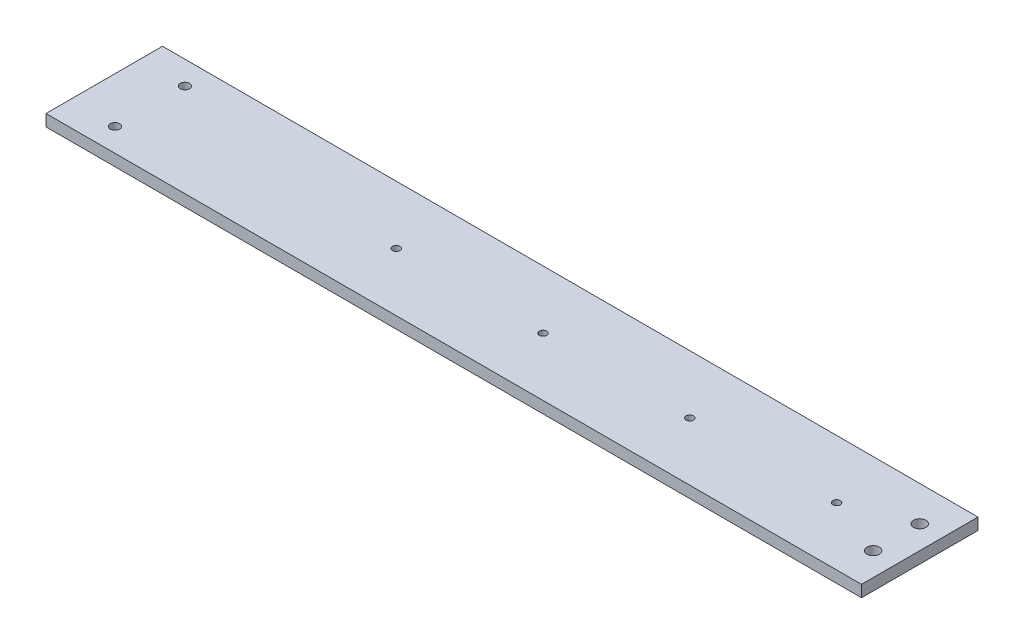
SolidWorks part; units mm, degrees
ref_plane "Front Plane" through (0, 0, 0) normal (0, 0, 1) x (1, 0, 0)
ref_plane "Top Plane" through (0, 0, 0) normal (0, 1, 0) x (1, 0, 0)
ref_plane "Right Plane" through (0, 0, 0) normal (1, 0, 0) x (0, 0, -1)
sketch "Sketch1" plane through (0, 0, 0) normal (0, 1, 0) x (1, 0, 0)
  line L1 (50.8, -25.4) -> (444.5, -25.4)
  line L2 (0, 0) -> (0, 12.7)
  line L3 (50.8, 38.1) -> (444.5, 38.1)
  line L4 (444.5, -25.4) -> (444.5, 38.1)
  line L6 (0, 0) -> (0, -25.4)
  line L7 (0, -25.4) -> (50.8, -25.4)
  line L10 (0, 12.7) -> (0, 38.1)
  line L11 (0, 38.1) -> (50.8, 38.1)
  dimension "D1" = 444.5
  dimension "D7" = 63.5
extrude "Boss-Extrude1" add sketch "Sketch1" along normal blind 6.35
sketch "Sketch2" plane through (0, 6.35, 0) normal (0, 1, 0) x (1, 0, 0)
  line L0 (0, 6.35) -> (444.5, 6.35) construction
  line L1 (0, 38.1) -> (0, -25.4) construction
  line L2 (444.5, -25.4) -> (444.5, 38.1) construction
  line L3 (431.8, -6.35) -> (431.8, 19.05) construction
  circle A0 centre (431.8, -6.35) radius 3.3734
  circle A1 centre (431.8, 19.05) radius 3.3734
  dimension "D1" = 6.7469
  dimension "D2" = 12.7
  dimension "D3" = 25.4
  dimension "D4" = 12.7
extrude "Cut-Extrude1" cut sketch "Sketch2" against normal through all
sketch "Sketch3" plane through (0, 6.35, 0) normal (0, 1, 0) x (1, 0, 0)
  line L0 (24.892, 25.4) -> (24.892, -12.7) construction
  line L1 (0, 38.1) -> (0, -25.4) construction
  circle A0 centre (24.892, 25.4) radius 1.27
  circle A1 centre (24.892, -12.7) radius 1.27
  point P6 (0, 6.35)
  point P7 (24.892, 6.35)
  dimension "D2" = 2.54
  dimension "D1" = 24.892
  dimension "D3" = 38.1
extrude "Cut-Extrude2" cut sketch "Sketch3" against normal through all
sketch "Sketch4" plane through (0, 6.35, 0) normal (0, 1, 0) x (-1, 0, 0)
  circle A0 centre (-159.18, -6.35) radius 0.9408
  circle A1 centre (-239.18, -6.35) radius 1.3067
hole_wizard "#10-32 Tapped Hole1" positions "Sketch5" profile "Sketch6" tap size "#10-32" standard "ANSI Inch" end condition through all
sketch "Sketch5" plane through (0, 6.35, 0) normal (0, 1, 0) x (-1, 0, 0)
  point P0 (-159.18, -6.35)
  point P3 (-239.18, -6.35)
  point P6 (-399.18, -6.35)
  point P8 (-319.18, -6.35)
  dimension "D1" = 160
  dimension "D2" = 80
sketch "Sketch6" plane through (159.18, 6.35, -6.35) normal (1, 0, 0) x (0, 0, 1)
  line L0 (0, 0) -> (0, 6.35)
  line L1 (0, 6.35) -> (2.0193, 6.35)
  line L2 (2.0193, 6.35) -> (2.0193, 0)
  line L5 (2.0193, 0) -> (0, 0)
  line L11 (0, -6.35) -> (0, 107.95) construction
  dimension "Thru Tap Drill Dia." = 4.0386
  dimension "Thru Tap Drill Depth" = 6.35
cosmetic thread "Hole Thread1" parameters "D2"=4.826
cosmetic thread "Hole Thread2" parameters "D2"=4.826
cosmetic thread "Hole Thread3" parameters "D2"=4.826
cosmetic thread "Hole Thread4" parameters "D2"=4.826
hole_wizard "1/4-20 Tapped Hole1" positions "Sketch7" profile "Sketch8" tap size "1/4-20" standard "ANSI Inch" end condition through all
sketch "Sketch7" plane through (0, 6.35, 0) normal (0, 1, 0) x (1, 0, 0)
  point P0 (24.892, -12.7)
  point P3 (24.892, 25.4)
sketch "Sketch8" plane through (24.892, 6.35, 12.7) normal (1, 0, 0) x (0, 0, 1)
  line L0 (0, 0) -> (0, 6.35)
  line L1 (0, 6.35) -> (2.5527, 6.35)
  line L2 (2.5527, 6.35) -> (2.5527, 0)
  line L5 (2.5527, 0) -> (0, 0)
  line L11 (0, -6.35) -> (0, 107.95) construction
  dimension "Thru Tap Drill Dia." = 5.1054
  dimension "Thru Tap Drill Depth" = 6.35
cosmetic thread "Hole Thread7" parameters "D2"=7.3406
cosmetic thread "Hole Thread8" parameters "D2"=6.35
